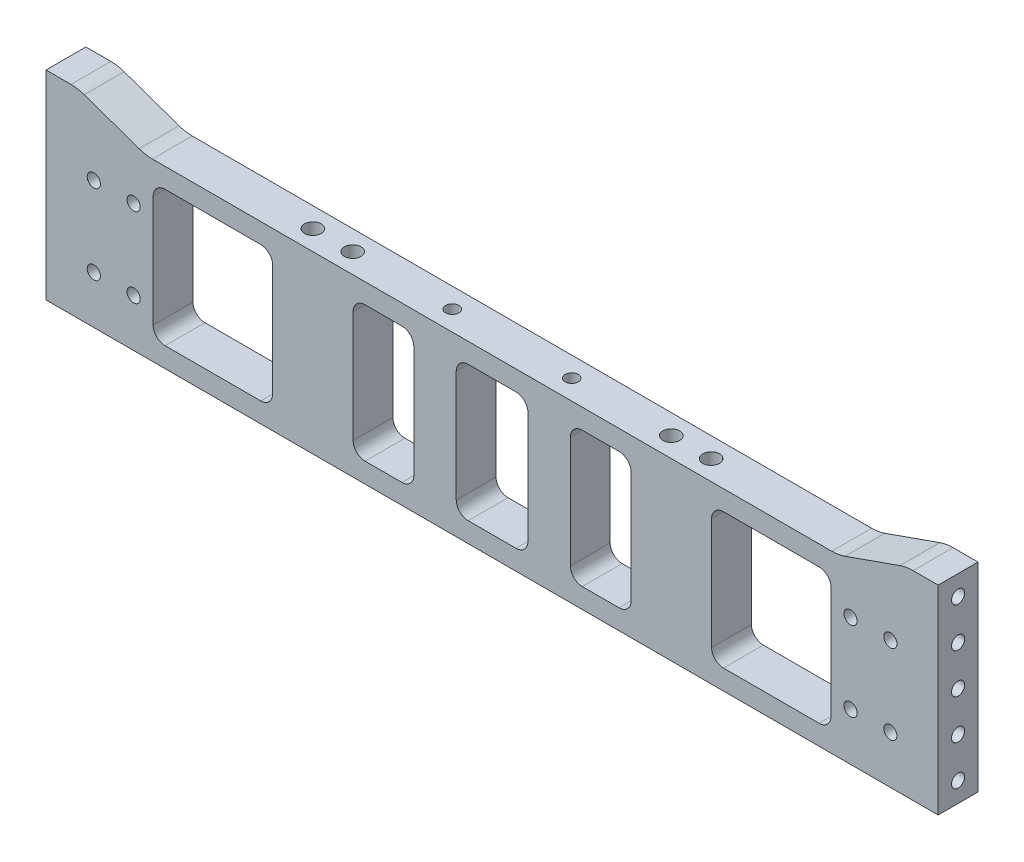
SolidWorks part; units mm, degrees
material "6061-T6 (SS)"
ref_plane "前视基准面" through (0, 0, 0) normal (0, 0, 1) x (1, 0, 0)
ref_plane "上视基准面" through (0, 0, 0) normal (0, 1, 0) x (1, 0, 0)
ref_plane "右视基准面" through (0, 0, 0) normal (1, 0, 0) x (0, 0, -1)
other "Configuration Table"
sketch "草图1" plane through (0, 0, 0) normal (0, 0, 1) x (1, 0, 0)
  line L1 (112, -22) -> (-112, -22)
  line L2 (112, -22) -> (112, 22)
  line L3 (112, 22) -> (-112, 22)
  line L4 (-112, -22) -> (-112, 22)
  line L5 (112, -22) -> (-112, 22) construction
  line L6 (112, 22) -> (-112, -22) construction
  point P0 (0, 0)
  dimension "D1" = 44
  dimension "D2" = 224
extrude "凸台-拉伸1" add sketch "草图1" along normal blind 10
sketch "草图2" plane through (0, 22, 0) normal (0, 1, 0) x (1, 0, 0)
  line L0 (112, 0) -> (-112, 0) construction
  line L1 (0, 0) -> (0, -10) construction
  line L2 (112, -10) -> (-112, -10) construction
  line L3 (-15, -5) -> (0, -5) construction
  circle A0 centre (-40, -5) radius 2.1
  circle A1 centre (-50, -5) radius 2.1
  circle A2 centre (50, -5) radius 2.1
  circle A3 centre (40, -5) radius 2.1
  circle A4 centre (-15, -5) radius 1.65
  circle A5 centre (15, -5) radius 1.65
  dimension "D1" = 4.2
  dimension "D2" = 40
  dimension "D3" = 5
  dimension "D5" = 3.3
  dimension "D4" = 2
  dimension "D6" = 15
extrude "切除-拉伸1" cut sketch "草图2" against normal through all
sketch "草图4" plane through (0, 0, 10) normal (0, 0, 1) x (1, 0, 0)
  line L0 (112, 22) -> (112, 28)
  line L1 (112, 28) -> (104, 28)
  line L2 (104, 28) -> (87, 22)
  line L3 (112, 22) -> (-112, 22) construction
  line L4 (87, 22) -> (112, 22)
  line L5 (0, 0) -> (0, 22) construction
  line L6 (-87, 22) -> (-112, 22)
  line L7 (-104, 28) -> (-87, 22)
  line L8 (-112, 28) -> (-104, 28)
  line L9 (-112, 22) -> (-112, 28)
  dimension "D1" = 28
  dimension "D2" = 25
  dimension "D3" = 8
extrude "凸台-拉伸2" add sketch "草图4" against normal blind 10
sketch "草图5" plane through (112, 0, 0) normal (1, 0, 0) x (0, 0, -1)
  line L0 (-5, 23) -> (-5, 28) construction
  line L1 (0, 28) -> (-10, 28) construction
  circle A0 centre (-5, 23) radius 1.65
  circle A1 centre (-5, 13) radius 1.65
  circle A2 centre (-5, 3) radius 1.65
  circle A3 centre (-5, -7) radius 1.65
  circle A4 centre (-5, -17) radius 1.65
  dimension "D1" = 3.3
  dimension "D3" = 40
  dimension "D4" = 5
  dimension "D2" = 5
extrude "切除-拉伸2" cut sketch "草图5" against normal blind 10
mirror "镜向1" about plane through (0, 0, 0) normal (1, 0, 0) of "切除-拉伸2"
sketch "草图6" plane through (0, 0, 10) normal (0, 0, 1) x (1, 0, 0)
  line L0 (-100, 10) -> (-100, -10) construction
  line L1 (-100, 0) -> (100, 0) construction
  line L2 (0, 0) -> (0, 22) construction
  line L3 (87, 22) -> (-87, 22) construction
  line L4 (100, 10) -> (100, -10) construction
  circle A0 centre (-100, 10) radius 1.65
  circle A1 centre (-100, -10) radius 1.65
  circle A2 centre (100, -10) radius 1.65
  circle A3 centre (100, 10) radius 1.65
  circle A4 centre (-90, 10) radius 1.65
  circle A5 centre (-90, -10) radius 1.65
  circle A6 centre (90, -10) radius 1.65
  circle A7 centre (90, 10) radius 1.65
  dimension "D1" = 3.3
  dimension "D2" = 3.3
  dimension "D3" = 20
  dimension "D4" = 100
  dimension "D5" = 2
extrude "切除-拉伸3" cut sketch "草图6" against normal through all
fillet "圆角1" radius 10 4 edges at (87, 22, 5) (104, 28, 5) (-87, 22, 5) (-104, 28, 5)
sketch "草图7" plane through (0, 0, 10) normal (0, 0, 1) x (1, 0, 0)
  line L0 (85.2871, 22) -> (-85.2871, 22) construction
  line L1 (-9, -17) -> (9, -17)
  line L2 (-9, -17) -> (-9, 17)
  line L3 (-9, 17) -> (9, 17)
  line L4 (9, -17) -> (9, 17)
  line L5 (-9, -17) -> (9, 17) construction
  line L6 (-9, 17) -> (9, -17) construction
  line L7 (0, 0) -> (27.275, 0) construction
  line L8 (0, 0) -> (0, -22) construction
  line L9 (19.65, -17) -> (34.9, -17)
  line L10 (19.65, -17) -> (19.65, 17)
  line L11 (19.65, 17) -> (34.9, 17)
  line L12 (34.9, -17) -> (34.9, 17)
  line L13 (19.65, -17) -> (34.9, 17) construction
  line L14 (19.65, 17) -> (34.9, -17) construction
  line L15 (-112, -22) -> (112, -22) construction
  line L16 (27.275, 0) -> (70.1, 0) construction
  line L17 (85.1, -17) -> (55.1, -17)
  line L18 (85.1, -17) -> (85.1, 17)
  line L19 (85.1, 17) -> (55.1, 17)
  line L20 (55.1, -17) -> (55.1, 17)
  line L21 (85.1, -17) -> (55.1, 17) construction
  line L22 (85.1, 17) -> (55.1, -17) construction
  line L23 (-85.1, 17) -> (-55.1, -17) construction
  line L24 (-85.1, -17) -> (-55.1, 17) construction
  line L25 (-27.275, 0) -> (-70.1, 0) construction
  line L26 (-19.65, 17) -> (-34.9, -17) construction
  line L27 (-19.65, -17) -> (-34.9, 17) construction
  line L28 (-55.1, -17) -> (-55.1, 17)
  line L29 (-85.1, 17) -> (-55.1, 17)
  line L30 (-85.1, -17) -> (-85.1, 17)
  line L31 (-85.1, -17) -> (-55.1, -17)
  line L32 (-34.9, -17) -> (-34.9, 17)
  line L33 (-19.65, 17) -> (-34.9, 17)
  line L34 (-19.65, -17) -> (-19.65, 17)
  line L35 (-19.65, -17) -> (-34.9, -17)
  point P0 (0, 0)
  point P14 (70.1, 0)
  point P36 (-70.1, 0)
  dimension "D1" = 5
  dimension "D2" = 18
  dimension "D3" = 3
  dimension "D4" = 3
  dimension "D5" = 5
  dimension "D6" = 5
  dimension "D7" = 3
  dimension "D8" = 30
extrude "切除-拉伸4" cut sketch "草图7" against normal through all
fillet "圆角2" radius 3 20 edges at (-9, -17, 5) (-9, 17, 5) (9, 17, 5) (9, -17, 5) (19.65, -17, 5) (19.65, 17, 5) (34.9, 17, 5) (34.9, -17, 5) (85.1, 17, 5) (85.1, -17, 5) (55.1, -17, 5) (55.1, 17, 5) (-55.1, 17, 5) (-55.1, -17, 5) (-85.1, -17, 5) (-34.9, -17, 5) (-34.9, 17, 5) (-19.65, 17, 5) (-19.65, -17, 5) (-85.1, 17, 5)
